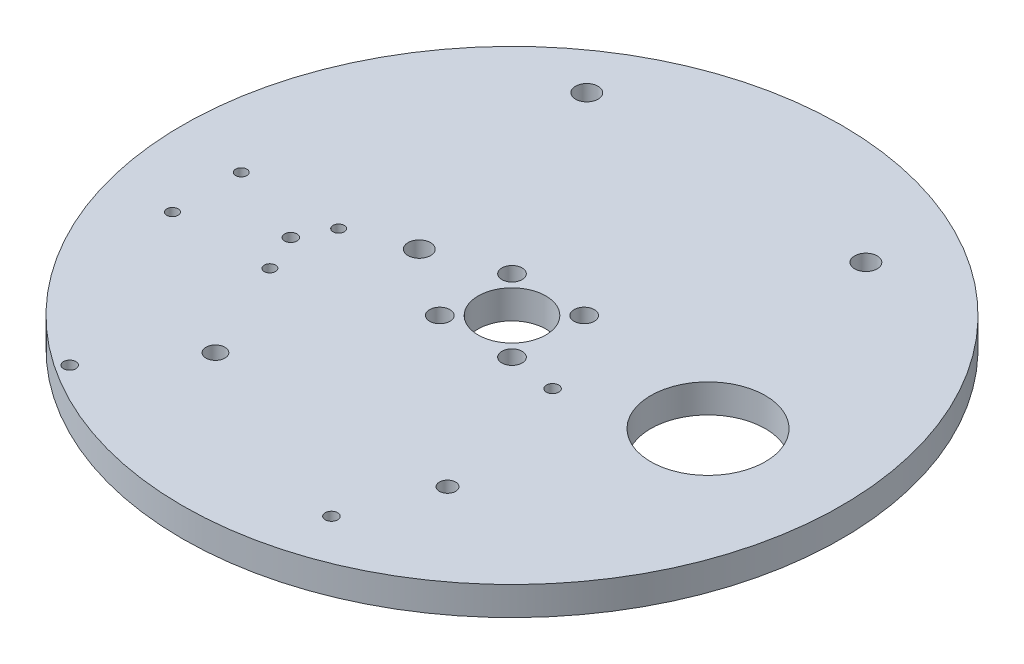
SolidWorks part; units mm, degrees
ref_plane "Front Plane" through (0, 0, 0) normal (0, 0, 1) x (1, 0, 0)
ref_plane "Top Plane" through (0, 0, 0) normal (0, 1, 0) x (1, 0, 0)
ref_plane "Right Plane" through (0, 0, 0) normal (1, 0, 0) x (0, 0, -1)
sketch "Sketch1" plane through (0, 0, 0) normal (0, 1, 0) x (1, 0, 0)
  circle A0 centre (0, 0) radius 73.025
  dimension "D1" = 146.05
extrude "Boss-Extrude1" add sketch "Sketch1" along normal blind 6.35
sketch "Sketch2" plane through (0, 6.35, 0) normal (0, 1, 0) x (1, 0, 0)
  circle A0 centre (0, 0) radius 7.5
  dimension "D1" = 15
extrude "Cut-Extrude1" cut sketch "Sketch2" against normal through all
sketch "Sketch3" plane through (0, 6.35, 0) normal (0, 1, 0) x (1, 0, 0)
  line L0 (0, -3.4925) -> (0, 3.4925) construction
  line L1 (-3.4925, 0) -> (3.4925, 0) construction
  arc A0 (-6, 8) -> (-10, 8) centre (-8, 8) ccw construction
  arc A1 (-6, 8) -> (-10, 8) centre (-8, 8) ccw
  arc A2 (-6, 8) -> (-10, 8) centre (-8, 8) ccw
  circle A3 centre (-8, 8) radius 2
  circle A4 centre (8, 8) radius 2
  circle A5 centre (8, -8) radius 2
  circle A6 centre (-8, -8) radius 2
  circle A7 centre (-8, 8) radius 2.25
  circle A8 centre (8, 8) radius 2.25
  circle A9 centre (8, -8) radius 2.25
  circle A10 centre (-8, -8) radius 2.25
  point P13 (0, 0)
  dimension "D1" = 4
extrude "Cut-Extrude2" cut sketch "Sketch3" against normal through all contours A1 A3 | A4 | A5 | A6 | A7 A3 A1 | A8 A4 | A9 A5 | A10 A6
sketch "Sketch4" plane through (0, 0, 0) normal (0, -1, 0) x (1, 0, 0)
  circle A0 centre (43.4342, 0) radius 12.7
  dimension "D1" = 25.4
extrude "Cut-Extrude3" cut sketch "Sketch4" against normal through all
sketch "Sketch5" plane through (0, 0, 0) normal (0, -1, 0) x (1, 0, 0)
  line L0 (-31.1, 37.9) -> (-25.7172, 37.9) construction
  line L1 (-25.7172, 42.1) -> (-31.1, 42.1) construction
  line L2 (25.7172, 37.9) -> (31.1, 37.9) construction
  line L3 (31.1, 42.1) -> (25.7172, 42.1) construction
  line L4 (-31.1, 37.9) -> (-25.7172, 37.9)
  line L5 (-25.7172, 42.1) -> (-31.1, 42.1)
  line L6 (25.7172, 37.9) -> (31.1, 37.9)
  line L7 (31.1, 42.1) -> (25.7172, 42.1)
  line L8 (-31.1, 42.1) -> (-31.1, 37.9)
  line L9 (31.1, 42.1) -> (31.1, 37.9)
  line L12 (25.7172, 41.8) -> (25.7172, 42.1)
  line L14 (25.7172, 38.2) -> (25.7172, 37.9)
  circle A0 centre (-35.87, 2.54) radius 1.25 construction
  circle A1 centre (-35.87, 17.78) radius 1.25 construction
  circle A2 centre (-57.46, 17.78) radius 1.25 construction
  circle A3 centre (-57.46, 2.54) radius 1.25 construction
  arc A12 (-25.7172, 37.9) -> (-25.7172, 42.1) centre (-25.7172, 40) ccw construction
  arc A13 (25.7172, 41.8) -> (25.7172, 38.2) centre (25.7172, 40) ccw construction
  circle A14 centre (-35.87, 2.54) radius 1.25
  circle A15 centre (-35.87, 17.78) radius 1.25
  circle A16 centre (-57.46, 17.78) radius 1.25
  circle A17 centre (-57.46, 2.54) radius 1.25
  arc A18 (19.9046, 9.5398) -> (17.1546, 9.5398) centre (18.5296, 9.5398) ccw
  arc A19 (17.1546, 9.5398) -> (19.9046, 9.5398) centre (18.5296, 9.5398) ccw
  arc A20 (-38.0954, 9.5398) -> (-40.8454, 9.5398) centre (-39.4704, 9.5398) ccw
  arc A21 (-40.8454, 9.5398) -> (-38.0954, 9.5398) centre (-39.4704, 9.5398) ccw
  arc A22 (-38.0954, 58.5398) -> (-40.8454, 58.5398) centre (-39.4704, 58.5398) ccw
  arc A23 (-40.8454, 58.5398) -> (-38.0954, 58.5398) centre (-39.4704, 58.5398) ccw
  arc A24 (17.1546, 58.5398) -> (19.9046, 58.5398) centre (18.5296, 58.5398) ccw
  arc A25 (19.9046, 58.5398) -> (17.1546, 58.5398) centre (18.5296, 58.5398) ccw
  arc A26 (-25.7172, 37.9) -> (-25.7172, 42.1) centre (-25.7172, 40) ccw
  arc A27 (25.7172, 41.8) -> (25.7172, 38.2) centre (25.7172, 40) ccw
  circle A28 centre (25.7172, 40) radius 1.8
  circle A29 centre (-25.7172, 40) radius 2.1
extrude "Cut-Extrude4" cut sketch "Sketch5" against normal through all contours A26 A29 | A16 | A20 A21 | A14 | A17 | A22 A23 | A24 A25 | A27 A28 | A18 A19 | A15
sketch "Sketch6" plane through (0, 6.35, 0) normal (0, 1, 0) x (1, 0, 0)
  circle A0 centre (-23.0043, 2.4604) radius 2.2225 construction
  circle A1 centre (29.0185, 49.3997) radius 2.2225 construction
  circle A2 centre (-34.4605, 51.0307) radius 2.2225 construction
  circle A3 centre (-23.0043, 2.4604) radius 2.2225
  circle A4 centre (29.0185, 49.3997) radius 2.2225
  circle A5 centre (-34.4605, 51.0307) radius 2.2225
  circle A6 centre (-34.4605, 51.0307) radius 2.5
  circle A7 centre (29.0185, 49.3997) radius 2.5
  circle A8 centre (-23.0043, 2.4604) radius 2.5
extrude "Cut-Extrude5" cut sketch "Sketch6" against normal through all contours A5 | A4 | A3 | A6 A5 | A7 A4 | A8 A3
